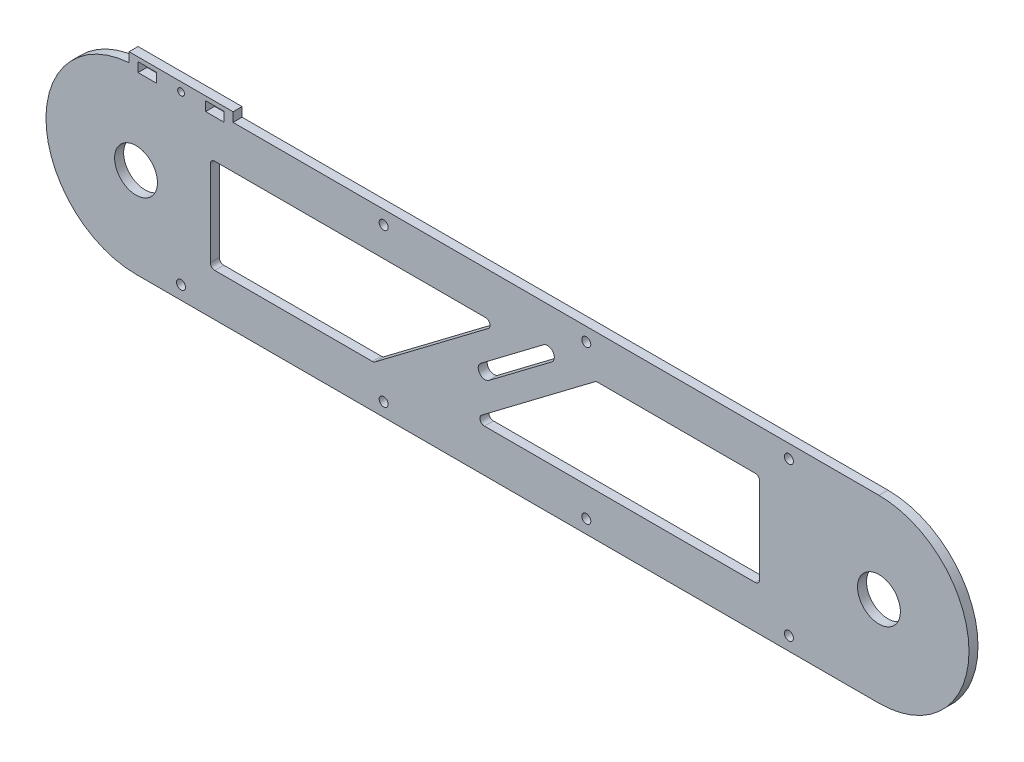
SolidWorks part; units mm, degrees
ref_plane "前视基准面" through (0, 0, 0) normal (0, 0, 1) x (1, 0, 0)
ref_plane "上视基准面" through (0, 0, 0) normal (0, 1, 0) x (1, 0, 0)
ref_plane "右视基准面" through (0, 0, 0) normal (1, 0, 0) x (0, 0, -1)
sketch "草图1" plane through (0, 0, 0) normal (0, 0, 1) x (1, 0, 0)
  line L0 (328.5429, -0.1457) -> (-1.4571, -0.1457) construction
  line L8 (328.5429, -40.1457) -> (-1.4571, -40.1457)
  line L9 (-1.4571, 39.8543) -> (328.5429, 39.8543)
  circle A0 centre (-1.4571, -0.1457) radius 9.52
  circle A1 centre (-1.4571, -0.1457) radius 40 construction
  arc A4 (-1.4571, 39.8543) -> (-1.4571, -40.1457) centre (-1.4571, -0.1457) ccw
  circle A11 centre (328.5429, -0.1457) radius 9.52
  circle A12 centre (328.5429, -0.1457) radius 40 construction
  circle A16 centre (328.5429, -0.1457) radius 30 construction
  arc A20 (328.5429, 39.8543) -> (328.5429, -40.1457) centre (328.5429, -0.1457) cw
  dimension "D1" = 330
  dimension "D2" = 19.04
  dimension "D4" = 19.04
  dimension "D5" = 80
extrude "凸台-拉伸1" add sketch "草图1" along normal blind 4
sketch "草图4" plane through (0, 0, 4) normal (0, 0, 1) x (1, 0, 0)
  line L1 (328.5429, 39.8543) -> (-1.4571, 39.8543) construction
  line L2 (41.6429, 35.3514) -> (-4.5571, 35.3514)
  line L3 (41.6429, 35.3514) -> (41.6429, 43.9543)
  line L4 (41.6429, 43.9543) -> (-4.5571, 43.9543)
  line L5 (-4.5571, 35.3514) -> (-4.5571, 43.9543)
  dimension "D1" = 46.2
  dimension "D2" = 3.1
  dimension "D3" = 4.1
extrude "凸台-拉伸2" add sketch "草图4" against normal blind 4
sketch "草图2" plane through (0, 0, 4) normal (0, 0, 1) x (1, 0, 0)
  line L0 (198.5429, 33.8543) -> (288.5429, 33.8543) construction
  line L1 (18.5429, 33.8543) -> (198.5429, 33.8543) construction
  line L2 (108.5429, -34.1457) -> (198.5429, 33.8543) construction
  line L3 (18.5429, 33.8543) -> (18.5429, -34.1457) construction
  line L4 (18.5429, -34.1457) -> (108.5429, -34.1457) construction
  line L5 (31.5429, -21.1457) -> (104.1839, -21.1457)
  line L6 (104.1839, -21.1457) -> (159.7721, 20.8543)
  line L7 (31.5429, 20.8543) -> (159.7721, 20.8543)
  line L8 (31.5429, 20.8543) -> (31.5429, -21.1457)
  line L9 (108.5429, -34.1457) -> (288.5429, -34.1457) construction
  line L10 (288.5429, -34.1457) -> (288.5429, 33.8543) construction
  line L12 (275.5429, 20.8543) -> (202.9018, 20.8543)
  line L13 (147.3136, -21.1457) -> (202.9018, 20.8543)
  line L14 (147.3136, -21.1457) -> (275.5429, -21.1457)
  line L15 (275.5429, -21.1457) -> (275.5429, 20.8543)
  line L20 (18.5429, 33.8543) -> (18.5429, 39.8543) construction
  line L28 (288.5429, 33.8543) -> (198.5429, 33.8543) construction
  line L30 (328.5429, 39.8543) -> (41.6429, 39.8543) construction
  line L31 (7.6429, 37.9143) -> (-0.5571, 42.1143) construction
  line L36 (29.4429, 42.1143) -> (37.6429, 42.1143)
  line L37 (29.4429, 42.1143) -> (29.4429, 37.9143)
  line L38 (29.4429, 37.9143) -> (37.6429, 37.9143)
  line L39 (37.6429, 42.1143) -> (37.6429, 37.9143)
  line L40 (29.4429, 42.1143) -> (37.6429, 37.9143) construction
  line L41 (29.4429, 37.9143) -> (37.6429, 42.1143) construction
  line L42 (7.6429, 42.1143) -> (-0.5571, 37.9143) construction
  line L43 (18.5429, 33.8543) -> (-161.4571, 33.8543) construction
  line L44 (-0.5571, 42.1143) -> (-0.5571, 37.9143)
  line L45 (7.6429, 37.9143) -> (-0.5571, 37.9143)
  line L46 (7.6429, 42.1143) -> (7.6429, 37.9143)
  line L47 (7.6429, 42.1143) -> (-0.5571, 42.1143)
  circle A1 centre (108.5429, 33.8543) radius 2
  circle A2 centre (198.5429, 33.8543) radius 2
  circle A3 centre (288.5429, 33.8543) radius 2
  circle A4 centre (108.5429, -34.1457) radius 2
  circle A5 centre (198.5429, -34.1457) radius 2
  circle A6 centre (288.5429, -34.1457) radius 2
  circle A7 centre (18.5429, -34.1457) radius 2
  circle A9 centre (18.5429, 40.0143) radius 1.5
  point P0 (3.5429, 40.0143)
  point P2 (-1.4571, -0.1457)
  point P30 (33.5429, 40.0143)
  dimension "D1" = 8.2
  dimension "D2" = 34
  dimension "D3" = 4.2
  dimension "D8" = 6.16
  dimension "D4" = 15
  dimension "D6" = 13
  dimension "D7" = 13
extrude "切除-拉伸1" cut sketch "草图2" against normal blind 4
sketch "草图3" plane through (0, 0, 4) normal (0, 0, 1) x (1, 0, 0)
  line L0 (202.9018, 20.8543) -> (159.7721, 20.8543) construction
  line L1 (147.3136, -21.1457) -> (104.1839, -21.1457) construction
  line L2 (181.337, 20.8543) -> (125.7487, -21.1457) construction
  line L3 (181.337, 20.8543) -> (153.5429, -0.1457) construction
  line L4 (183.1455, 18.4607) -> (155.3514, -2.5393)
  line L5 (179.5285, 23.2479) -> (151.7344, 2.2479)
  arc A0 (183.1455, 18.4607) -> (179.5285, 23.2479) centre (181.337, 20.8543) ccw
  arc A1 (151.7344, 2.2479) -> (155.3514, -2.5393) centre (153.5429, -0.1457) ccw
  point P11 (167.4399, 10.3543)
extrude "切除-拉伸2" cut sketch "草图3" against normal blind 10
fillet "圆角1" radius 2 8 edges at (275.5429, -21.1457, 2) (275.5429, 20.8543, 2) (202.9018, 20.8543, 2) (147.3136, -21.1457, 2) (104.1839, -21.1457, 2) (159.7721, 20.8543, 2) (31.5429, -21.1457, 2) (31.5429, 20.8543, 2)
